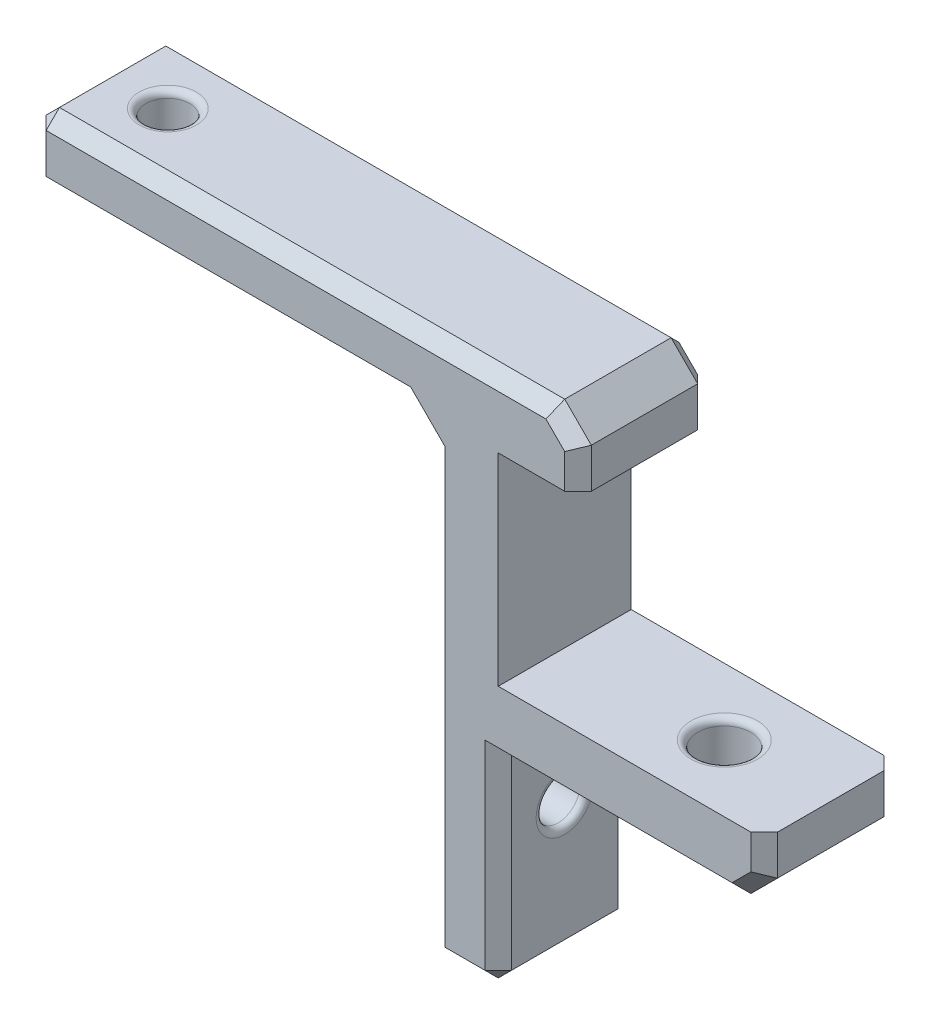
SolidWorks part; units mm, degrees
ref_plane "Plano frontal" through (0, 0, 0) normal (0, 0, 1) x (1, 0, 0)
ref_plane "Plano superior" through (0, 0, 0) normal (0, 1, 0) x (1, 0, 0)
ref_plane "Plano direito" through (0, 0, 0) normal (1, 0, 0) x (0, 0, -1)
sketch "Esboço1" plane through (0, 0, 0) normal (0, 0, 1) x (1, 0, 0)
  line L1 (-0.1136, 14.25) -> (-6.1136, 14.25)
  line L3 (-6.1136, -0.95) -> (13.8864, -0.95)
  line L4 (13.8864, -0.95) -> (13.8864, -5.95)
  line L5 (13.8864, -5.95) -> (-6.1136, -5.95)
  line L6 (-11.1136, -20.95) -> (-11.1136, 14.25)
  line L7 (-0.1136, 19.25) -> (-0.1136, 14.25)
  line L9 (-6.1136, 14.25) -> (-6.1136, -0.95)
  line L15 (-0.1136, 19.25) -> (-41.1136, 19.25)
  line L16 (-41.1136, 19.25) -> (-41.1136, 14.25)
  line L17 (-41.1136, 14.25) -> (-11.1136, 14.25)
  line L19 (-11.1136, -20.95) -> (-6.1136, -20.95)
  line L20 (-6.1136, -20.95) -> (-6.1136, -5.95)
  dimension "D1" = 5
  dimension "D2" = 20
  dimension "D3" = 15.2
  dimension "D4" = 6
  dimension "D5" = 5
  dimension "D6" = 5
  dimension "D7" = 0
  dimension "D8" = 5
  dimension "D9" = 30
  dimension "D10" = 15
extrude "Ressalto-extrusão1" add sketch "Esboço1" along normal blind 10
sketch "Esboço3" plane through (0, -5.95, 0) normal (0, -1, 0) x (1, 0, 0)
  line L0 (13.8864, 5) -> (5.8864, 5) construction
  line L1 (13.8864, 10) -> (13.8864, 0) construction
  circle A0 centre (5.8864, 5) radius 2
  dimension "D1" = 4
  dimension "D2" = 8
extrude "Corte-extrusão1" cut sketch "Esboço3" against normal blind 15
chamfer "Chanfro1" distance 1.6 angle 45 1 edges at (5.8864, -5.95, 3)
fillet "Filete1" radius 0.5 1 edges at (7.8864, -0.95, 5)
chamfer "Chanfro5" distance 2 angle 45 3 edges at (13.8864, -5.95, 5) (-11.1136, 14.25, 5) (-0.1136, 19.25, 5)
chamfer "Chanfro8" distance 1 angle 45 28 edges at (-41.1136, 19.25, 5) (-41.1136, 16.75, 10) (-41.1136, 14.25, 5) (-41.1136, 16.75, 0) (-0.1136, 15.75, 0) (-21.6136, 19.25, 0) (13.8864, -2.45, 0) (12.8864, -4.95, 0) (2.8864, -5.95, 0) (-11.1136, -4.35, 0) (-12.1136, 13.25, 0) (-27.1136, 14.25, 0) (13.8864, -2.45, 10) (12.8864, -4.95, 10) (2.8864, -5.95, 10) (-11.1136, -4.35, 10) (-12.1136, 13.25, 10) (-27.1136, 14.25, 10) (-0.1136, 15.75, 10) (-21.6136, 19.25, 10) (-1.1136, 18.25, 0) (-1.1136, 18.25, 10) (-11.1136, -20.95, 5) (-8.6136, -20.95, 10) (-6.1136, -13.45, 10) (-6.1136, -20.95, 5) (-6.1136, -13.45, 0) (-8.6136, -20.95, 0)
sketch "Esboço4" plane through (0, 19.25, 0) normal (0, 1, 0) x (1, 0, 0)
  line L0 (-40.1136, -5) -> (-35.9636, -5) construction
  line L1 (-40.1136, -1) -> (-40.1136, -9) construction
  circle A0 centre (-35.9636, -5) radius 1.65
  dimension "D1" = 3.3
  dimension "D2" = 4.15
extrude "Corte-extrusão2" cut sketch "Esboço4" against normal blind 10
fillet "Filete2" radius 0.5 2 edges at (-37.6136, 14.25, 5) (-35.9636, 19.25, 6.65)
sketch "Esboço5" plane through (-11.1136, 0, 0) normal (-1, 0, 0) x (0, 0, 1)
  line L0 (5, -20.95) -> (5, -10.95) construction
  line L1 (9, -20.95) -> (1, -20.95) construction
  circle A0 centre (5, -10.95) radius 1.65
  dimension "D1" = 3.3
  dimension "D2" = 10
extrude "Corte-extrusão3" cut sketch "Esboço5" against normal blind 10 contours A0
fillet "Filete3" radius 0.5 2 edges at (-6.1136, -10.95, 6.65) (-11.1136, -10.95, 6.65)
